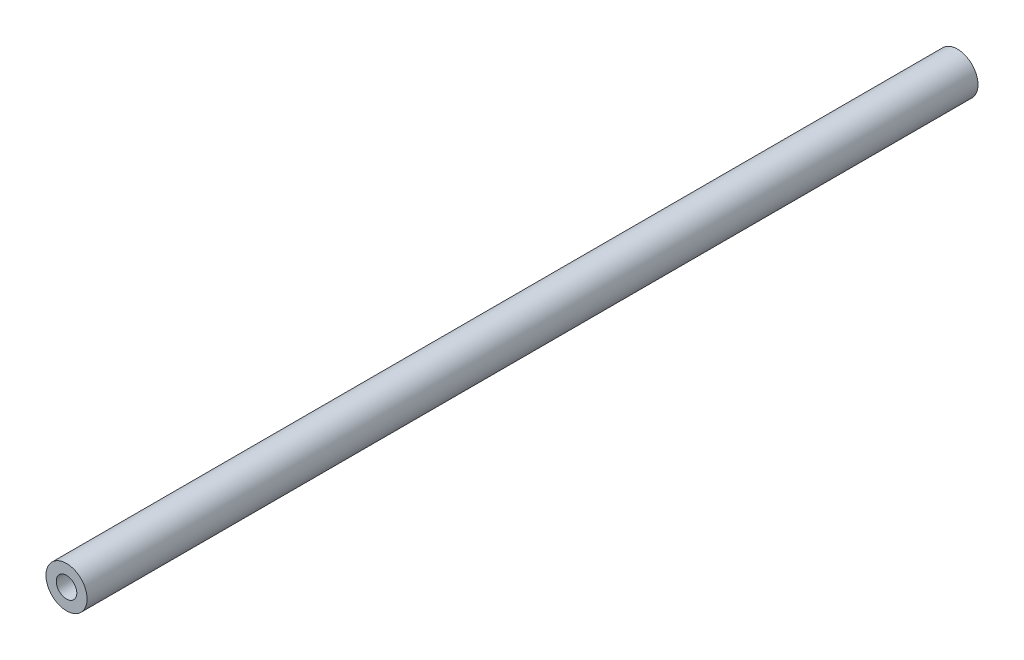
SolidWorks part; units mm, degrees
ref_plane "前视基准面" through (0, 0, 0) normal (0, 0, 1) x (1, 0, 0)
ref_plane "上视基准面" through (0, 0, 0) normal (0, 1, 0) x (1, 0, 0)
ref_plane "右视基准面" through (0, 0, 0) normal (1, 0, 0) x (0, 0, -1)
sketch "草图1" plane through (0, 0, 0) normal (0, 0, 1) x (1, 0, 0)
  circle A0 centre (0, 0) radius 3
  circle A1 centre (0, 0) radius 1.5
extrude "凸台-拉伸1" add sketch "草图1" along normal blind 130
